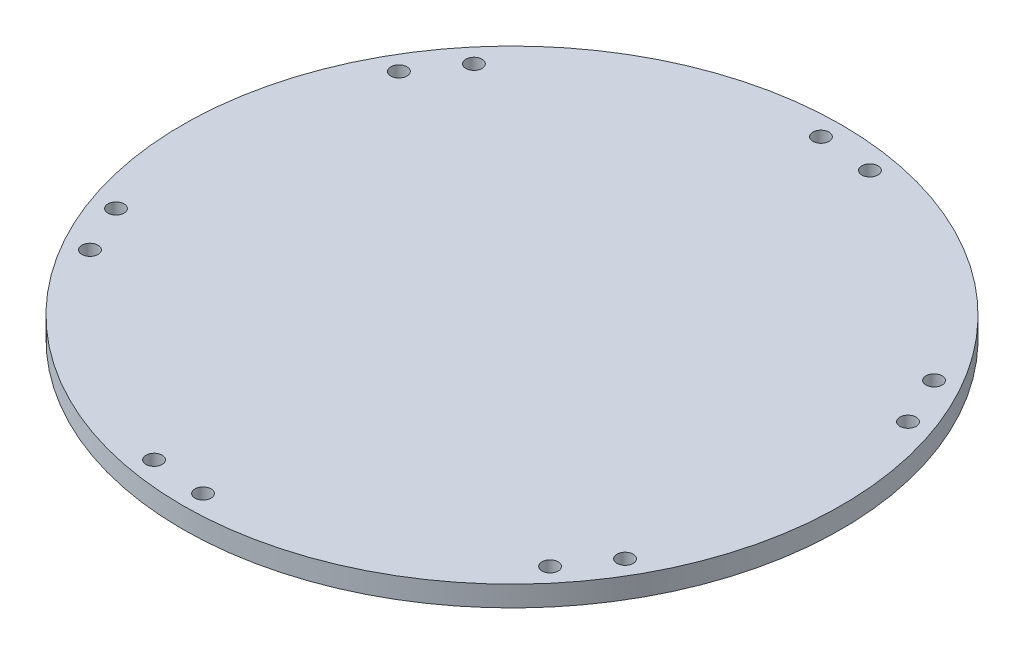
SolidWorks part; units mm, degrees
material "6061 Alloy"
ref_plane "Front Plane" through (0, 0, 0) normal (0, 0, 1) x (1, 0, 0)
ref_plane "Top Plane" through (0, 0, 0) normal (0, 1, 0) x (1, 0, 0)
ref_plane "Right Plane" through (0, 0, 0) normal (1, 0, 0) x (0, 0, -1)
sketch "Back Plate Main" plane through (0, 0, 0) normal (0, 1, 0) x (1, 0, 0)
  line L0 (0, 0) -> (16.54, 93.8029) construction
  line L1 (0, 0) -> (0, 95.25) construction
  circle A0 centre (0, 0) radius 101.6
  point P3 (0, 95.25)
  point P7 (16.54, 93.8029)
  point P10 (82.4889, 47.625)
  point P11 (89.5057, 32.5774)
  point P12 (82.4889, -47.625)
  point P13 (72.9657, -61.2255)
  point P14 (0, -95.25)
  point P15 (-16.54, -93.8029)
  point P16 (-82.4889, -47.625)
  point P17 (-89.5057, -32.5774)
  point P18 (-82.4889, 47.625)
  point P19 (-72.9657, 61.2255)
  point P20 (0, 0)
  dimension "D1" = 203.2
  dimension "D2" = 95.25
  dimension "D3" = 95.25
  dimension "D4" = 10
  dimension "D5" = 6
extrude "Boss-Extrude1" add sketch "Back Plate Main" against normal blind 6.35
hole_wizard "#9 (0.196) Diameter Hole1" positions "Sketch3" profile "Sketch4" hole size "#9" standard "ANSI Inch" end condition through all
sketch "Sketch3" plane through (0, 0, 0) normal (0, 1, 0) x (1, 0, 0)
  point P0 (0, 95.25)
  point P3 (82.4889, 47.625)
  point P6 (82.4889, -47.625)
  point P9 (0, -95.25)
  point P12 (-82.4889, -47.625)
  point P15 (-82.4889, 47.625)
  point P19 (-72.9657, 61.2255)
  point P22 (16.54, 93.8029)
  point P25 (89.5057, 32.5774)
  point P28 (72.9657, -61.2255)
  point P31 (-16.54, -93.8029)
  point P34 (-89.5057, -32.5774)
sketch "Sketch4" plane through (0, 0, -95.25) normal (1, 0, 0) x (0, 0, 1)
  line L0 (0, 0) -> (0, 6.35)
  line L1 (0, 6.35) -> (2.4892, 6.35)
  line L2 (2.4892, 6.35) -> (2.4892, 0)
  line L5 (2.4892, 0) -> (0, 0)
  line L11 (0, -6.35) -> (0, 107.95) construction
  dimension "Thru Hole Dia." = 4.9784
  dimension "Thru Hole Depth" = 6.35
sketch "Clearance Cutout" plane through (0, -6.35, 0) normal (0, -1, 0) x (1, 0, 0)
  circle A0 centre (0, 0) radius 25.4
  dimension "D1" = 50.8
extrude "Cut-Extrude1" cut sketch "Clearance Cutout" against normal blind 3.81
